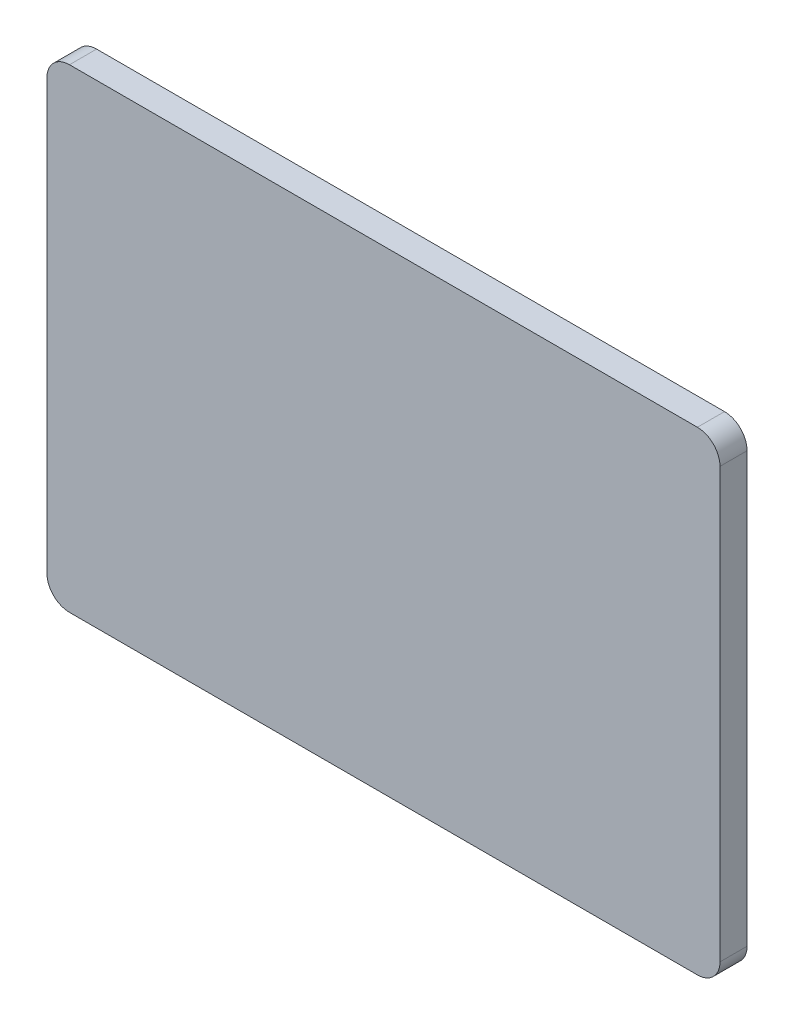
SolidWorks part; units mm, degrees
ref_plane "Plan de face" through (0, 0, 0) normal (0, 0, 1) x (1, 0, 0)
ref_plane "Plan de dessus" through (0, 0, 0) normal (0, 1, 0) x (1, 0, 0)
ref_plane "Plan de droite" through (0, 0, 0) normal (1, 0, 0) x (0, 0, -1)
sketch "Esquisse1" plane through (0, 0, 0) normal (0, 0, 1) x (1, 0, 0)
  line L1 (0, 0) -> (298, 0)
  line L2 (0, 0) -> (0, 210)
  line L3 (0, 210) -> (298, 210)
  line L4 (298, 0) -> (298, 210)
  dimension "D1" = 210
  dimension "D2" = 298
extrude "Boss.-Extru.1" add sketch "Esquisse1" along normal blind 12
fillet "Congé1" radius 10 4 edges at (0, 0, 6) (298, 0, 6) (298, 210, 6) (0, 210, 6)
